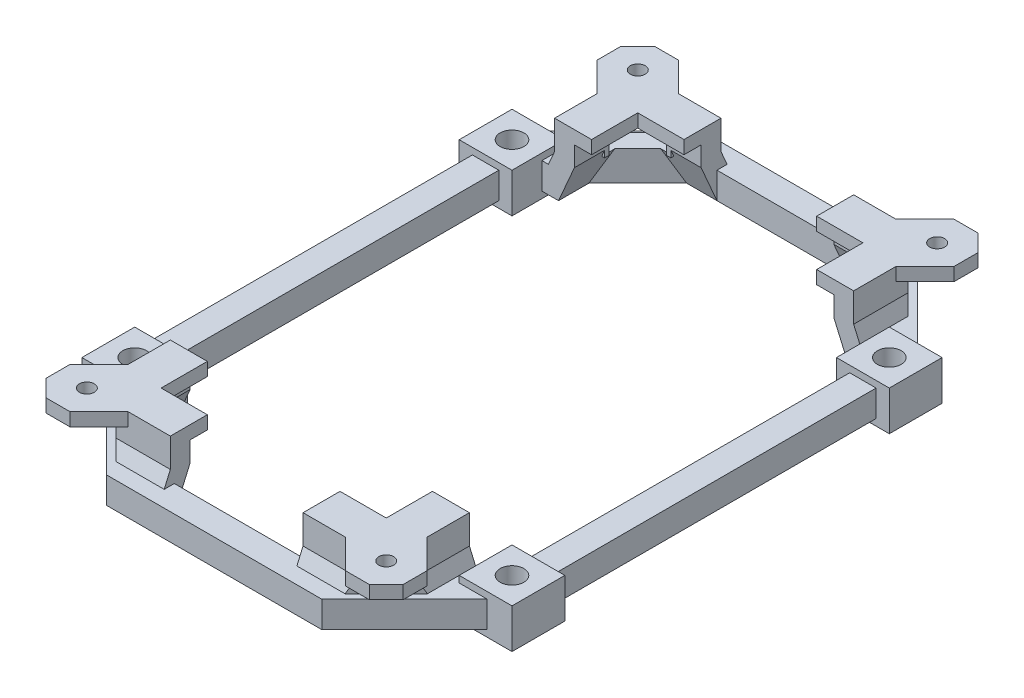
SolidWorks part; units mm, degrees
ref_plane "Front Plane" through (0, 0, 0) normal (0, 0, 1) x (1, 0, 0)
ref_plane "Top Plane" through (0, 0, 0) normal (0, 1, 0) x (1, 0, 0)
ref_plane "Right Plane" through (0, 0, 0) normal (1, 0, 0) x (0, 0, -1)
sketch "Sketch1" plane through (0, 0, 0) normal (0, 1, 0) x (1, 0, 0)
  line L0 (-53.15, 0) -> (-61.15, 0)
  line L1 (-61.15, 0) -> (-61.15, -49.15)
  line L2 (-61.15, -49.15) -> (-65.15, -49.15)
  line L3 (-65.15, -49.15) -> (-65.15, -65.15)
  line L4 (-65.15, -65.15) -> (-57.6353, -65.15)
  line L6 (-57.6353, -65.15) -> (-32.5853, -90.2)
  line L17 (-53.15, 0) -> (-53.15, -49.15)
  line L18 (-53.15, -49.15) -> (-49.15, -49.15)
  line L19 (-49.15, -49.15) -> (-49.15, -58.2)
  line L24 (-53.15, 0) -> (0, 0) construction
  line L25 (0, 0) -> (0, -92.25) construction
  line L26 (-39.3, -58.2) -> (-38.1, -58.2) construction
  line L27 (-38.1, 0) -> (-38.1, -76.2) construction
  line L28 (-65.15, -57.15) -> (-49.15, -57.15) construction
  line L29 (-38.1, -76.2) -> (0, -76.2) construction
  line L37 (-38.1, -76.2) -> (-39.3, -77.4) construction
  line L38 (-39.3, -77.4) -> (-39.3, -58.2) construction
  line L39 (-49.15, -58.2) -> (-39.3, -58.2)
  line L41 (-39.3, -77.4) -> (-20.1, -77.4) construction
  line L42 (-20.1, -77.4) -> (-20.1, -82.2)
  line L44 (-32.5853, -90.2) -> (0, -90.2)
  line L45 (0, -90.2) -> (0, -82.2)
  line L46 (0, -82.2) -> (-20.1, -82.2)
  line L47 (-39.3, -58.2) -> (-39.3, -72.1716)
  line L49 (-34.0716, -77.4) -> (-20.1, -77.4)
  line L50 (-20.1, -77.4) -> (-20.1, -76.2) construction
  line L51 (-39.3, -72.1716) -> (-34.0716, -77.4)
  line L52 (-39.3, -72.1716) -> (-49.15, -62.3216) construction
  line L53 (-49.15, -62.3216) -> (-49.15, -58.2) construction
  point P37 (-57.15, 0)
  dimension "D1" = 8
  dimension "D2" = 16
  dimension "D4" = 57.15
  dimension "D5" = 57.15
  dimension "D6" = 76.2
  dimension "D7" = 38.1
  dimension "D8" = 45
  dimension "D10" = 6
  dimension "D9" = 18
  dimension "D3" = 1.2
  dimension "D11" = 135
  dimension "D12" = 2
  dimension "D13" = 6
extrude "Boss-Extrude1" add sketch "Sketch1" along normal blind 8
sketch "Sketch2" plane through (0, 0, 0) normal (0, -1, 0) x (1, 0, 0)
  line L0 (-49.15, 58.2) -> (-49.15, 49.15) construction
  line L1 (-65.15, 49.15) -> (-65.15, 65.15) construction
  line L2 (-49.15, 58.2) -> (-49.15, 49.15)
  line L3 (-65.15, 49.15) -> (-65.15, 65.15)
  line L5 (-65.15, 49.15) -> (-49.15, 49.15)
  line L6 (-65.15, 65.15) -> (-49.15, 65.15)
  line L7 (-49.15, 65.15) -> (-49.15, 58.2)
extrude "Boss-Extrude2" add sketch "Sketch2" along normal blind 2
sketch "Sketch3" plane through (0, 8, 0) normal (0, 1, 0) x (1, 0, 0)
  line L4 (-39.3, -58.2) -> (-45.3, -58.2)
  line L6 (-45.3, -58.2) -> (-45.3, -74.6569)
  line L9 (-20.1, -83.4) -> (-20.1, -77.4)
  line L10 (-45.3, -74.6569) -> (-36.5569, -83.4)
  line L11 (-36.5569, -83.4) -> (-20.1, -83.4)
  line L12 (-57.6353, -65.15) -> (-32.5853, -90.2) construction
  line L13 (-39.3, -58.2) -> (-39.3, -72.1716)
  line L14 (-39.3, -72.1716) -> (-34.0716, -77.4)
  line L15 (-34.0716, -77.4) -> (-20.1, -77.4)
  line L16 (-20.1, -77.4) -> (-34.0716, -77.4) construction
  line L17 (-39.3, -72.1716) -> (-39.3, -58.2) construction
  line L18 (-39.3, -58.2) -> (-49.15, -58.2) construction
  line L19 (-20.1, -82.2) -> (-20.1, -77.4) construction
  line L20 (-39.3, -72.1716) -> (-43.5426, -76.4142) construction
  line L21 (-39.3, -72.1716) -> (-45.3, -72.1716) construction
  dimension "D1" = 6
extrude "Boss-Extrude3" add sketch "Sketch3" along normal blind 9.05
sketch "Sketch4" plane through (0, 17.05, 0) normal (0, 1, 0) x (1, 0, 0)
  line L0 (-45.3, -58.2) -> (-34.1, -58.2)
  line L1 (-34.1, -58.2) -> (-34.1, -72.2)
  line L2 (-34.1, -72.2) -> (-20.1, -72.2)
  line L3 (-20.1, -72.2) -> (-20.1, -83.4)
  line L4 (-20.1, -83.4) -> (-32.9256, -83.4)
  line L5 (-36.5569, -83.4) -> (-20.1, -83.4) construction
  line L6 (-32.9256, -83.4) -> (-41.7235, -92.1978)
  line L7 (-41.7235, -92.1978) -> (-48.9722, -92.1978)
  line L8 (-48.9722, -92.1978) -> (-54.0978, -87.0722)
  line L9 (-54.0978, -87.0722) -> (-54.0978, -79.8235)
  line L10 (-54.0978, -79.8235) -> (-45.3, -71.0256)
  line L11 (-45.3, -71.0256) -> (-45.3, -58.2)
  line L12 (-45.3478, -83.4478) -> (-51.535, -89.635) construction
  line L13 (-45.3478, -83.4478) -> (-54.0978, -83.4478) construction
  line L14 (-43.7569, -81.8569) -> (-40.9284, -79.0284) construction
  line L15 (-45.3, -74.6569) -> (-36.5569, -83.4) construction
  line L16 (-53.126, -78.8517) -> (-40.7517, -91.226) construction
  circle A0 centre (-45.3478, -83.4478) radius 2.25
  dimension "D4" = 4.5
  dimension "D1" = 11.2
  dimension "D2" = 135
  dimension "D3" = 135
  dimension "D6" = 4
  dimension "D5" = 6.5
extrude "Boss-Extrude4" add sketch "Sketch4" along normal blind 4
sketch "Sketch5" plane through (-59.9784, 0, 59.9784) normal (-0.7071, 0, 0.7071) x (0.7071, 0, 0.7071)
  line L0 (20.7584, 17.05) -> (20.7584, 8) construction
  line L1 (20.7584, 17.05) -> (33.1231, 17.05)
  line L2 (20.7584, 17.05) -> (20.7584, 9.05)
  line L3 (20.7584, 9.05) -> (33.1231, 9.05)
  line L4 (33.1231, 17.05) -> (33.1231, 9.05)
  line L5 (33.1231, 17.05) -> (33.1231, 8) construction
  line L6 (20.7584, 17.05) -> (33.1231, 17.05) construction
  dimension "D1" = 8
extrude "Cut-Extrude1" cut sketch "Sketch5" against normal up to next and the other way through all
sketch "Sketch7" plane through (0, 0, 0) normal (0, -1, 0) x (1, 0, 0)
  line L0 (-32.5853, 90.2) -> (-29.2716, 82.2) construction
  line L1 (-29.449, 82.0226) -> (-34.9685, 76.5031) construction
  line L2 (-29.2716, 82.2) -> (0, 82.2) construction
  line L3 (0, 82.2) -> (-20.1, 82.2) construction
  line L4 (-57.6353, 65.15) -> (-32.5853, 90.2) construction
  line L5 (-32.5853, 90.2) -> (0, 90.2) construction
sketch "Sketch6" plane through (-20.1, 0, 0) normal (1, 0, 0) x (0, 0, -1)
  line L1 (-82.2, 0) -> (-77.4, 11.05)
  line L2 (-77.4, 17.05) -> (-77.4, 0) construction
  line L3 (-77.4, 11.05) -> (-77.4, 0)
  line L5 (-77.4, 17.05) -> (-72.2, 17.05) construction
  line L8 (-82.2, 0) -> (-77.4, 0)
  dimension "D1" = 6
extrude "Cut-Extrude2" cut sketch "Sketch6" against normal up to vertex (9.1716 mm away) up to point (-29.2716, 0, 82.2)
ref_plane "Plane1" through (19.05, 0, 19.05) normal (0.7071, 0, 0.7071) x (0.7071, 0, -0.7071)
mirror "Mirror1" about plane through (19.05, 0, 19.05) normal (0.7071, 0, 0.7071) of "Cut-Extrude2"
sketch "Sketch8" plane through (19.05, 0, 19.05) normal (0.7071, 0, 0.7071) x (0.7071, 0, -0.7071)
  line L8 (-78.8223, 0) -> (-78.8223, 9.05)
  line L9 (-78.8223, 9.05) -> (-75.4282, 9.05)
  line L10 (-75.4282, 9.05) -> (-75.4282, 0)
  line L11 (-75.4282, 0) -> (-78.8223, 0)
  line L12 (-75.4282, 0) -> (-75.4282, 11.05) construction
  line L13 (-84.8223, 9.05) -> (-76.337, 9.05) construction
extrude "Cut-Extrude3" cut sketch "Sketch8" against normal up to surface and the other way up to surface up to face at (-41.7, 5.525, 62.7858) other way up to face at (-24.6858, 5.525, 79.8)
sketch "Sketch10" plane through (-20.1, 0, 0) normal (1, 0, 0) x (0, 0, -1)
  line L0 (-83.4, 12.2969) -> (-85.2665, 8)
  line L1 (-85.2665, 8) -> (-83.4, 8)
  line L2 (-83.4, 8) -> (-83.4, 12.2969)
  line L3 (-83.4, 21.05) -> (-83.4, 8) construction
  line L4 (-90.2, 8) -> (-82.2, 8) construction
  line L5 (-77.4, 11.05) -> (-82.2, 0) construction
  line L6 (-78.2688, 9.05) -> (-82.2, 0) construction
  dimension "D1" = 6
extrude "Boss-Extrude5" add sketch "Sketch10" against normal up to vertex (16.4569 mm away)
sketch "Sketch11" plane through (19.05, 0, 19.05) normal (0.7071, 0, 0.7071) x (0.7071, 0, -0.7071)
  line L0 (-84.8223, 12.2969) -> (-86.1421, 8)
  line L1 (-86.1421, 8) -> (-84.8223, 8)
  line L2 (-84.8223, 8) -> (-84.8223, 12.2969)
  line L3 (-84.8223, 9.05) -> (-84.8223, 8) construction
  line L4 (-86.1421, 8) -> (-84.8223, 8) construction
  line L5 (-84.8223, 12.2969) -> (-86.1421, 8) construction
extrude "Cut-Extrude4" cut sketch "Sketch11" along normal through all
mirror "Mirror2" about plane through (19.05, 0, 19.05) normal (0.7071, 0, 0.7071) of "Cut-Extrude4", "Boss-Extrude5"
sketch "Sketch12" plane through (0, 8, 0) normal (0, 1, 0) x (1, 0, 0)
  line L0 (-65.15, -65.15) -> (-49.15, -49.15) construction
  circle A0 centre (-57.15, -57.15) radius 3.6
  point P7 (-57.15, -57.15)
  dimension "D1" = 7.2
extrude "Cut-Extrude5" cut sketch "Sketch12" against normal through all
mirror "Mirror3" about plane through (-53.15, 8, 0) normal (0, 0, 1) of bodies 112
mirror "Mirror4" about plane through (0, 8, -90.2) normal (-1, 0, 0) of bodies 113
sketch "Sketch13" plane through (0, 8, 0) normal (0, 1, 0) x (1, 0, 0)
  line L0 (-49.15, 49.15) -> (-53.15, 49.15) construction
  line L1 (-65.15, 65.15) -> (-49.15, 65.15)
  line L2 (-65.15, 65.15) -> (-65.15, 49.15)
  line L3 (-65.15, 49.15) -> (-49.15, 49.15)
  line L4 (-49.15, 65.15) -> (-49.15, 49.15)
  line L5 (-65.15, -49.15) -> (-49.15, -49.15)
  line L6 (-65.15, -49.15) -> (-65.15, -65.15)
  line L7 (-65.15, -65.15) -> (-49.15, -65.15)
  line L8 (-49.15, -49.15) -> (-49.15, -65.15)
  line L9 (49.15, -49.15) -> (65.15, -49.15)
  line L10 (49.15, -49.15) -> (49.15, -65.15)
  line L11 (49.15, -65.15) -> (65.15, -65.15)
  line L12 (65.15, -49.15) -> (65.15, -65.15)
  line L13 (49.15, 65.15) -> (65.15, 65.15)
  line L14 (49.15, 65.15) -> (49.15, 49.15)
  line L15 (49.15, 49.15) -> (65.15, 49.15)
  line L16 (65.15, 65.15) -> (65.15, 49.15)
  line L17 (-49.15, 58.2) -> (-49.15, 49.15) construction
  line L18 (-65.15, -65.15) -> (-57.6353, -65.15) construction
  line L19 (-65.15, -49.15) -> (-65.15, -65.15) construction
  line L20 (-49.15, -58.2) -> (-49.15, -49.15) construction
  line L21 (-49.15, -49.15) -> (-53.15, -49.15) construction
  line L22 (65.15, -65.15) -> (57.6353, -65.15) construction
  line L23 (61.15, -49.15) -> (65.15, -49.15) construction
  line L24 (65.15, -49.15) -> (65.15, -65.15) construction
  line L25 (49.15, -58.2) -> (49.15, -49.15) construction
  line L26 (65.15, 65.15) -> (57.6353, 65.15) construction
  line L27 (61.15, 49.15) -> (65.15, 49.15) construction
  line L28 (49.15, 58.2) -> (49.15, 49.15) construction
  line L29 (65.15, 49.15) -> (65.15, 65.15) construction
  line L30 (-65.15, 49.15) -> (-65.15, 65.15) construction
  line L31 (-65.15, 65.15) -> (-57.6353, 65.15) construction
  circle A0 centre (57.15, 57.15) radius 3.6 construction
  circle A1 centre (57.15, -57.15) radius 3.6 construction
  circle A2 centre (-57.15, -57.15) radius 3.6 construction
  circle A3 centre (-57.15, 57.15) radius 3.6 construction
  circle A4 centre (57.15, 57.15) radius 3.6
  circle A5 centre (57.15, -57.15) radius 3.6
  circle A6 centre (-57.15, -57.15) radius 3.6
  circle A7 centre (-57.15, 57.15) radius 3.6
extrude "Boss-Extrude6" add sketch "Sketch13" along normal blind 2
ref_plane "Plane2" through (0, 0, 74.7858) normal (0, 0, -1) x (-1, 0, 0)
sketch "Sketch14" plane through (0, 0, 74.7858) normal (0, 0, -1) x (-1, 0, 0)
  line L0 (39.3, 17.05) -> (-39.3, 17.05) construction
  line L1 (39.3, 17.05) -> (-37.4285, 0) construction
  line L3 (20.1, 17.05) -> (30.5569, 17.05) construction
  line L4 (39.3, 9.05) -> (39.3, 17.05) construction
  line L5 (-39.3, 9.05) -> (-39.3, 17.05) construction
  line L8 (29.2716, 0) -> (44.1, 0) construction
  line L9 (-38.8918, 9.05) -> (-29.2716, 9.05)
  line L10 (-29.2716, 9.05) -> (-29.2716, 0)
  line L11 (-29.2716, 0) -> (-37.4285, 0)
  line L12 (-33.2028, 9.05) -> (-40.1688, 9.05) construction
  arc A1 (-39.3, 17.05) -> (-37.4285, 0) centre (39.3, 17.05) ccw construction
  arc A2 (-38.8918, 9.05) -> (-37.4285, 0) centre (39.3, 17.05) ccw
  point P14 (0, 0)
  point P18 (0, 0)
  point P19 (-32.9702, -5.7357)
  point P20 (0, 0)
  point P21 (-36.2512, -5.2979)
  point P22 (0, 0)
extrude "Cut-Extrude6" cut sketch "Sketch14" against normal up to surface (2.6142 mm away) and the other way blind 15 up to face at (26.6428, 12.3833, 77.4)
equation "\"sample_clearance\"= 1.2'sample to edge wall"
equation "\"truss_width\"= 8'f"
equation "\"truss_height\" = 8'thickness"
equation "\"truss_offset\" = 2'height offset from baseplate"
equation "\"D1@Sketch1\"=\"truss_width\""
equation "\"screw_spacing_short\"= 4.5in'baseplate spacing parallel to sample short side"
equation "\"screw_spacing_long\"= 4.5in'baseplate spacing parallel to sample long side"
equation "\"truss_bore_width\"= 16'box around bore hole"
equation "\"D2@Sketch1\"=\"truss_bore_width\""
equation "\"D4@Sketch1\"=\"screw_spacing_long\"/2"
equation "\"D5@Sketch1\"=\"screw_spacing_short\"/2"
equation "\"sample_long\"= 6in"
equation "\"sample_short\"= 3in"
equation "\"D6@Sketch1\"=\"sample_long\"/2"
equation "\"D7@Sketch1\"=\"sample_short\"/2"
equation "\"base_clearance_corner\"= 2"
equation "\"wall\"= 12"
equation "\"sample_short_to_truss\"= 6"
equation "\"D10@Sketch1\"=\"sample_short_to_truss\""
equation "\"D1@Boss-Extrude1\"=\"truss_height\""
equation "\"D1@Boss-Extrude2\"=\"truss_offset\""
equation "\"D1@Boss-Extrude3\"=0.75in - \"truss_offset\" - \"truss_height\""
equation "\"D3@Sketch1\"=\"sample_clearance\""
equation "\"D1@Sketch4\"=\"sample_clearance\"+10"
equation "\"D1@Boss-Extrude6\"=12-\"truss_offset\"-\"truss_height\""
